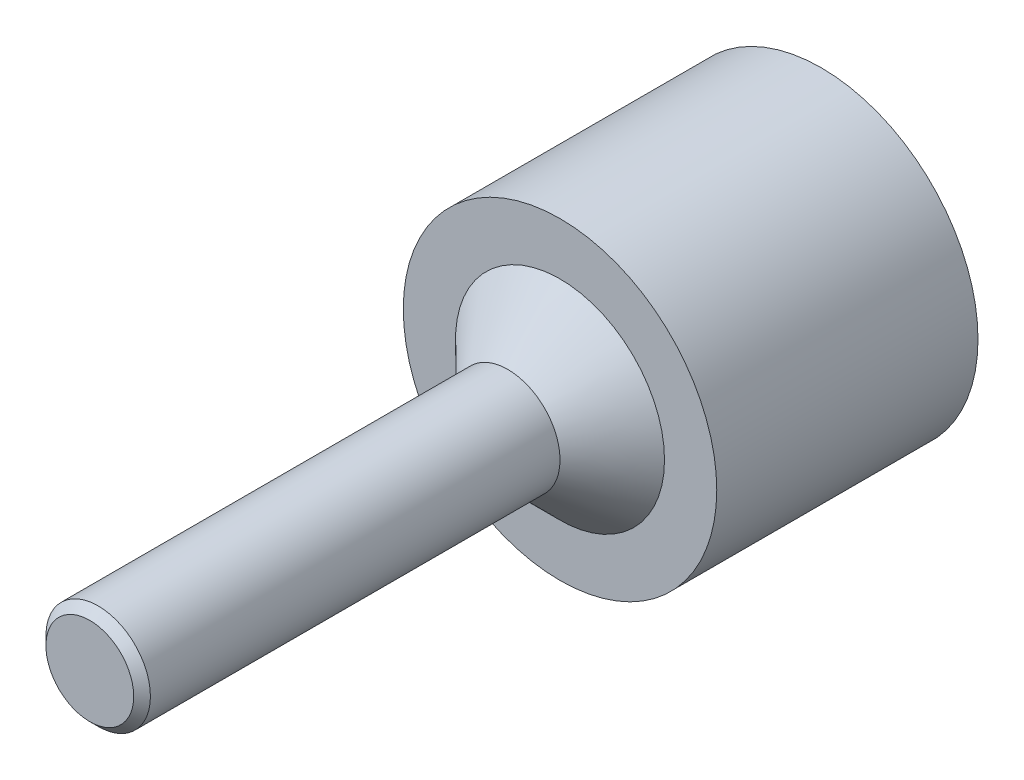
SolidWorks part; units mm, degrees
material "6061 Alloy"
ref_plane "Front Plane" through (0, 0, 0) normal (0, 0, 1) x (1, 0, 0)
ref_plane "Top Plane" through (0, 0, 0) normal (0, 1, 0) x (1, 0, 0)
ref_plane "Right Plane" through (0, 0, 0) normal (1, 0, 0) x (0, 0, -1)
sketch "Sketch" plane through (0, 0, 0) normal (1, 0, 0) x (0, 0, -1)
  line L0 (0, 0) -> (0, 3.175)
  line L1 (0, 3.175) -> (28.575, 3.175)
  line L2 (28.575, 3.175) -> (28.575, 9.525)
  line L3 (28.575, 9.525) -> (44.45, 9.525)
  line L4 (44.45, 9.525) -> (44.45, 0)
  line L7 (44.45, 0) -> (0, 0)
  dimension "D1" = 3.175
  dimension "D3" = 9.525
  dimension "D5" = 15.875
  dimension "D6" = 44.45
revolve "Shaft" add sketch "Sketch" angle 360 about L7
sketch "Sketch4" plane through (0, 0, -44.45) normal (0, 0, -1) x (-1, 0, 0)
  circle A0 centre (0, 0) radius 6.35
  dimension "D1" = 12.7
extrude "Shaft Bore" cut sketch "Sketch4" against normal blind 12.7
ref_plane "Set Screw Reference Plane" through (0, -9.525, 0) normal (0, -1, 0) x (-1, 0, 0)
hole_wizard "#4-40 Tapped Hole1" positions "Sketch3" profile "Sketch2" tap size "#4-40" standard "ANSI Inch"
sketch "Sketch3" plane through (0, -9.525, 0) normal (0, -1, 0) x (-1, 0, 0)
  line L3 (9.525, 44.45) -> (-9.525, 44.45) construction
  line L4 (0, 28.575) -> (0, 44.45) construction
  line L5 (-9.525, 28.575) -> (9.525, 28.575) construction
  point P8 (0, 34.925)
  point P10 (0, 41.275)
  dimension "D1" = 3.175
  dimension "D2" = 9.525
sketch "Sketch2" plane through (0, -9.525, -34.925) normal (1, 0, 0) x (0, 0, -1)
  line L0 (0, 0) -> (0, 3.175)
  line L1 (0, 3.175) -> (1.1303, 3.175)
  line L2 (1.1303, 3.175) -> (1.1303, 0)
  line L5 (1.1303, 0) -> (0, 0)
  line L11 (0, -6.35) -> (0, 107.95) construction
  dimension "Thru Tap Drill Dia." = 2.2606
  dimension "Thru Tap Drill Depth" = 3.175
cosmetic thread "Hole Thread1" parameters "D1"=0, "D2"=3.2606
cosmetic thread "Hole Thread2" parameters "D1"=0, "D2"=3.2606
chamfer "Chamfer1" distance 0.508 angle 45 1 edges at (-3.175, 0, 0)
chamfer "Chamfer2" distance 3.175 angle 45 1 edges at (-3.175, 0, -28.575)
chamfer "Chamfer3" distance 0.508 angle 45 1 edges at (-6.35, 0, -44.45)
